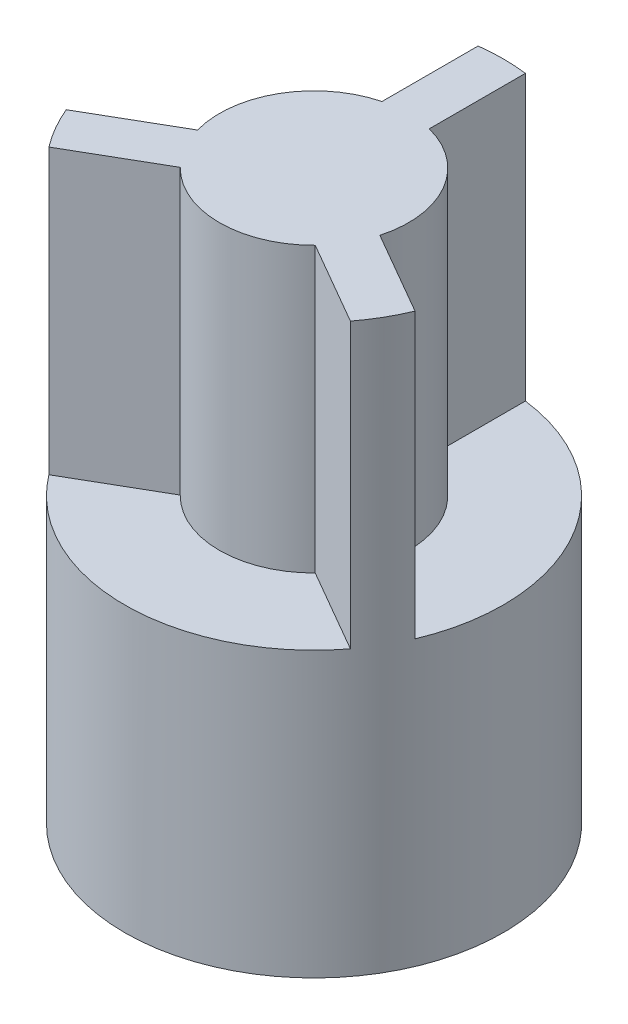
SolidWorks part; units mm, degrees
ref_plane "Front Plane" through (0, 0, 0) normal (0, 0, 1) x (1, 0, 0)
ref_plane "Top Plane" through (0, 0, 0) normal (0, 1, 0) x (1, 0, 0)
ref_plane "Right Plane" through (0, 0, 0) normal (1, 0, 0) x (0, 0, -1)
sketch "Sketch1" plane through (0, 0, 0) normal (0, 1, 0) x (1, 0, 0)
  circle A0 centre (0, 0) radius 4
  dimension "D1" = 8
extrude "Boss-Extrude1" add sketch "Sketch1" along normal blind 6
sketch "Sketch2" plane through (0, 6, 0) normal (0, 1, 0) x (1, 0, 0)
  circle A0 centre (0, 0) radius 2
  dimension "D1" = 4
extrude "Boss-Extrude2" add sketch "Sketch2" along normal blind 6
sketch "Sketch3" plane through (0, 6, 0) normal (0, 1, 0) x (1, 0, 0)
  line L0 (0, 0) -> (0, 4) construction
  line L1 (0, 0) -> (3.4641, -2) construction
  line L2 (0, 0) -> (-3.4641, -2) construction
  line L3 (-0.5, 3.9686) -> (-0.5, 0.2887)
  line L4 (-0.5, 0.2887) -> (-3.6869, -1.5513)
  line L5 (0.5, 3.9686) -> (0.5, 0.2887)
  line L6 (0.5, 0.2887) -> (3.6869, -1.5513)
  line L7 (-3.1869, -2.4173) -> (0, -0.5774)
  line L8 (0, -0.5774) -> (3.1869, -2.4173)
  line L9 (-3.6869, -1.5513) -> (-3.4369, -1.9843) construction
  line L10 (-3.1869, -2.4173) -> (-3.4369, -1.9843) construction
  line L11 (3.6869, -1.5513) -> (3.4369, -1.9843) construction
  line L12 (3.1869, -2.4173) -> (3.4369, -1.9843) construction
  circle A0 centre (0, 0) radius 4 construction
  arc A1 (0.5, 3.9686) -> (-0.5, 3.9686) centre (0, 0) ccw
  arc A2 (-3.6869, -1.5513) -> (-3.1869, -2.4173) centre (0, 0) ccw
  arc A3 (3.1869, -2.4173) -> (3.6869, -1.5513) centre (0, 0) ccw
  dimension "D2" = 120
  dimension "D3" = 120
  dimension "D4" = 120
  dimension "D5" = 0.5
  dimension "D6" = 0.5
  dimension "D7" = 0.5
  dimension "D8" = 0.5
  dimension "D9" = 0.5
  dimension "D10" = 0.5
  dimension "D1" = 3
extrude "Boss-Extrude3" add sketch "Sketch3" along normal blind 6
equation "\"GuideRailThickness\"=0.5"
equation "\"D5@Sketch3\"=\"GuideRailThickness\""
